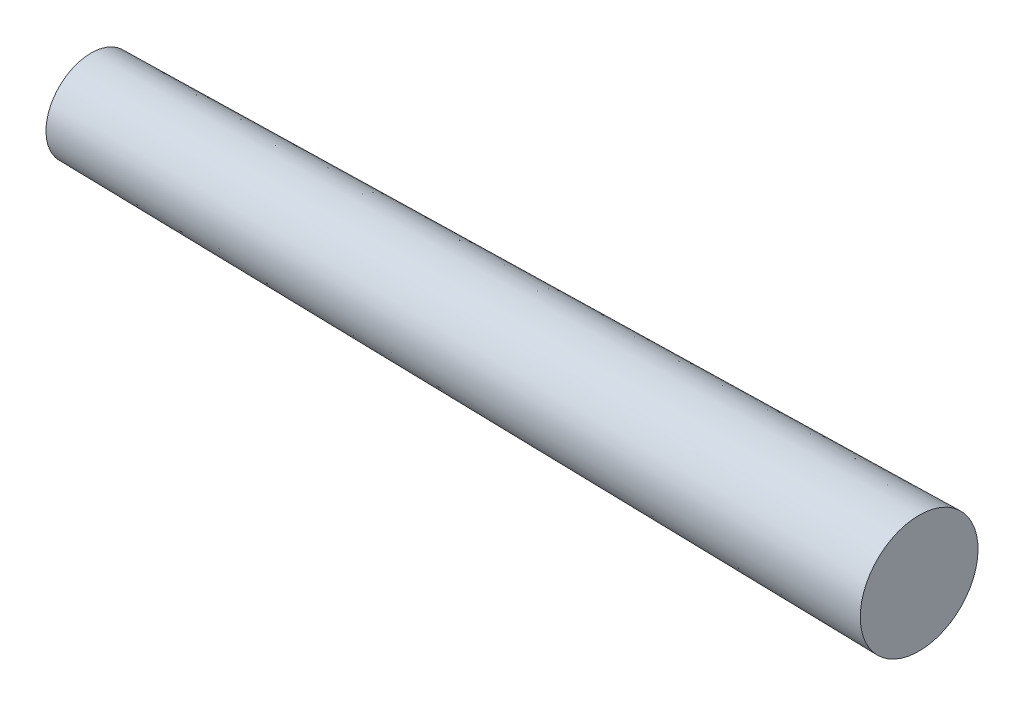
SolidWorks part; units mm, degrees
ref_plane "Ebene vorne" through (0, 0, 0) normal (0, 0, 1) x (1, 0, 0)
ref_plane "Ebene oben" through (0, 0, 0) normal (0, 1, 0) x (1, 0, 0)
ref_plane "Ebene rechts" through (0, 0, 0) normal (1, 0, 0) x (0, 0, -1)
sketch "Skizze1" plane through (0, 0, 0) normal (0, 0, 1) x (1, 0, 0)
  line L0 (-10.5382, 0) -> (-10.5382, 2.5)
  line L1 (-10.5382, 2.5) -> (79.4618, 4)
  line L2 (79.4618, 4) -> (79.4618, 0)
  line L3 (79.4618, 0) -> (-10.5382, 0)
  dimension "D1" = 2.5
  dimension "D2" = 4
  dimension "D3" = 90
revolve "Rotation1" add sketch "Skizze1" angle 360 about L3
sketch "Skizze4" plane through (79.4618, 0, 0) normal (1, 0, 0) x (0, 0, -1)
  circle A0 centre (0, 0) radius 4.175
extrude "Schnitt-Linear austragen1" cut sketch "Skizze4" against normal blind 5
sketch "Skizze7" plane through (74.4618, 0, 0) normal (1, 0, 0) x (0, 0, -1)
  circle A0 centre (0, 0) radius 4.375
extrude "Schnitt-Linear austragen3" cut sketch "Skizze7" against normal blind 5
sketch "Skizze8" plane through (-10.5382, 0, 0) normal (-1, 0, 0) x (0, 0, 1)
  circle A0 centre (0, 0) radius 3.5435
extrude "Schnitt-Linear austragen4" cut sketch "Skizze8" against normal blind 5
sketch "Skizze9" plane through (0, 0, 0) normal (0, 0, 1) x (1, 0, 0)
  line L0 (69.4618, 3.8333) -> (69.4618, 5.3333)
  line L1 (69.4618, 5.3333) -> (-5.5382, 4.0833)
  line L2 (-5.5382, 4.0833) -> (-5.5382, 2.5833)
  line L3 (69.4618, 3.8333) -> (-5.5382, 2.5833)
  line L4 (69.4618, 0) -> (-5.5382, 0) construction
  line L5 (69.4618, -3.8333) -> (69.4618, 3.8333) construction
  line L6 (-5.5382, 2.5833) -> (-5.5382, -2.5833) construction
  dimension "D1" = 1.5
  dimension "D2" = 1.5
revolve "Rotation2" add sketch "Skizze9" angle 360 about L4
